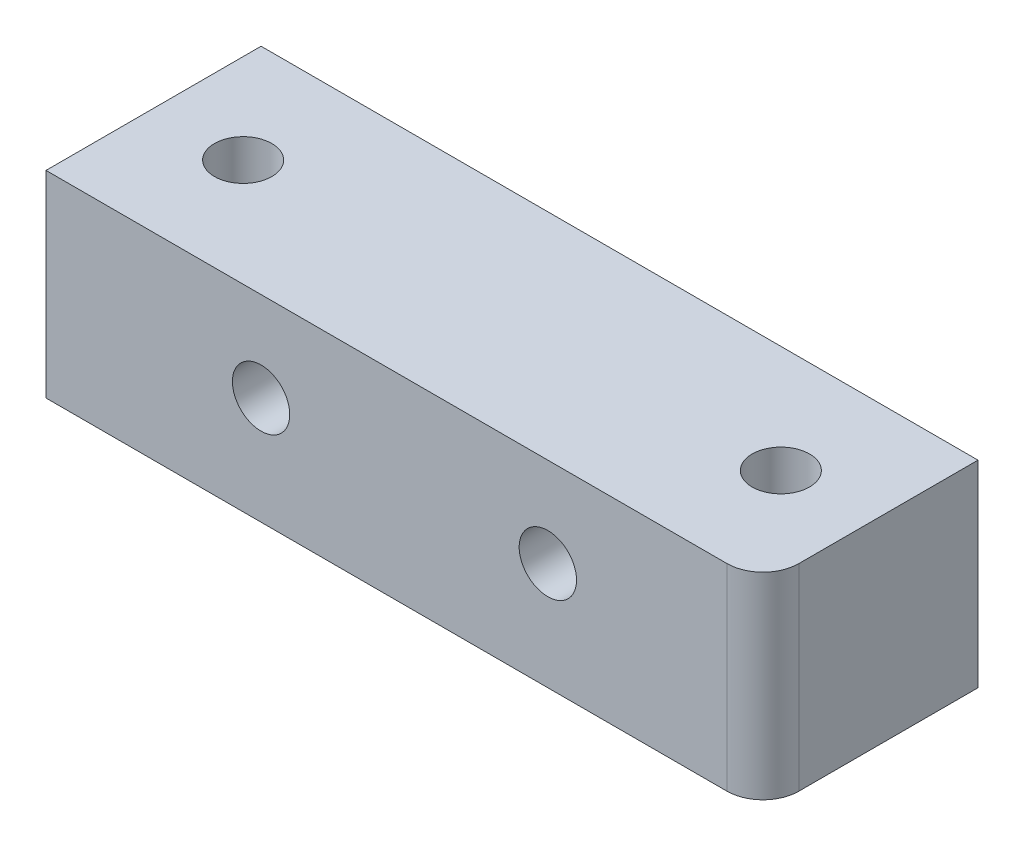
SolidWorks part; units mm, degrees
ref_plane "Front Plane" through (0, 0, 0) normal (0, 0, 1) x (1, 0, 0)
ref_plane "Top Plane" through (0, 0, 0) normal (0, 1, 0) x (1, 0, 0)
ref_plane "Right Plane" through (0, 0, 0) normal (1, 0, 0) x (0, 0, -1)
sketch "Sketch1" plane through (0, 0, 0) normal (0, 1, 0) x (1, 0, 0)
  line L1 (-10, -3) -> (10, -3)
  line L2 (-10, -3) -> (-10, 3)
  line L3 (-10, 3) -> (10, 3)
  line L4 (10, -3) -> (10, 3)
  line L5 (-10, -3) -> (10, 3) construction
  line L6 (-10, 3) -> (10, -3) construction
  point P0 (0, 0)
  dimension "D1" = 20
  dimension "D2" = 6
extrude "Boss-Extrude1" add sketch "Sketch1" against normal blind 5.5
hole_wizard "M2x0.4 Tapped Hole2" positions "Sketch4" profile "Sketch3" tap size "M2x0.4" standard "Ansi Metric" end condition up to next
sketch "Sketch4" plane through (0, 0, 0) normal (0, 1, 0) x (-1, 0, 0)
  line L0 (-10, 3) -> (-10, -3) construction
  line L1 (-10, -3) -> (10, -3) construction
  line L2 (10, -3) -> (10, 3) construction
  point P0 (7.5, 0)
  point P1 (-7.5, 0)
  dimension "D1" = 2.5
  dimension "D2" = 3
  dimension "D3" = 2.5
sketch "Sketch3" plane through (-7.5, 0, 0) normal (1, 0, 0) x (0, 0, 1)
  line L0 (0, 0) -> (0, 5.5)
  line L1 (0, 5.5) -> (0.8, 5.5)
  line L2 (0.8, 5.5) -> (0.8, 0)
  line L5 (0.8, 0) -> (0, 0)
  line L11 (0, -6.35) -> (0, 107.95) construction
  dimension "Thru Tap Drill Dia." = 1.6
  dimension "Thru Tap Drill Depth" = 5.5
cosmetic thread "Hole Thread1" parameters "D2"=2
cosmetic thread "Hole Thread2" parameters "D2"=2
fillet "Fillet1" radius 1 1 edges at (10, -2.75, 3)
hole_wizard "M2x0.4 Tapped Hole1" positions "Sketch6" profile "Sketch5" tap size "M2x0.4" standard "Ansi Metric" end condition up to next
sketch "Sketch6" plane through (0, 0, 3) normal (0, 0, 1) x (1, 0, 0)
  line L2 (-10, -5.5) -> (9, -5.5) construction
  line L3 (10, 0) -> (10, -5.5) construction
  point P0 (-4, -2.5)
  point P1 (4, -2.5)
  dimension "D1" = 8
  dimension "D2" = 3
  dimension "D3" = 6
sketch "Sketch5" plane through (-4, -2.5, 3) normal (1, 0, 0) x (0, -1, 0)
  line L0 (0, 0) -> (0, 6)
  line L1 (0, 6) -> (0.8, 6)
  line L2 (0.8, 6) -> (0.8, 0)
  line L5 (0.8, 0) -> (0, 0)
  line L11 (0, -6.35) -> (0, 107.95) construction
  dimension "Thru Tap Drill Dia." = 1.6
  dimension "Thru Tap Drill Depth" = 6
cosmetic thread "Hole Thread3" parameters "D2"=2
cosmetic thread "Hole Thread4" parameters "D2"=2
